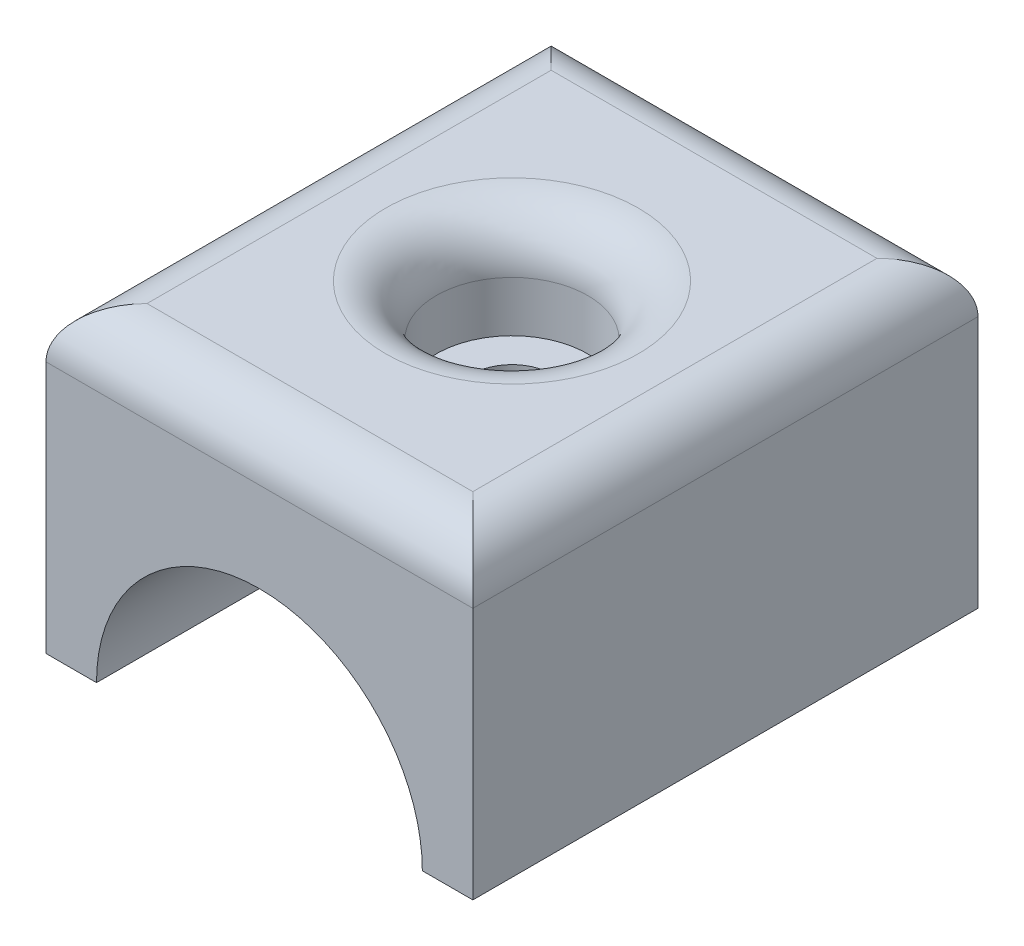
SolidWorks part; units mm, degrees
ref_plane "Front Plane" through (0, 0, 0) normal (0, 0, 1) x (1, 0, 0)
ref_plane "Top Plane" through (0, 0, 0) normal (0, 1, 0) x (1, 0, 0)
ref_plane "Right Plane" through (0, 0, 0) normal (1, 0, 0) x (0, 0, -1)
sketch "Sketch2" plane through (0, 0, 0) normal (0, 0, 1) x (1, 0, 0)
  line L0 (0, 0) -> (-2, 0)
  line L1 (-2, 0) -> (-2, 12)
  line L2 (-2, 12) -> (14.9, 12)
  line L3 (14.9, 12) -> (14.9, 0)
  line L4 (14.9, 0) -> (12.9, 0)
  arc A0 (0, 0) -> (12.9, 0) centre (6.45, 0) cw
  dimension "D1" = 6.45
  dimension "D2" = 2
  dimension "D3" = 2
  dimension "D4" = 12
extrude "Boss-Extrude1" add sketch "Sketch2" against normal blind 20
ref_plane "Plane1" through (0, 12, 0) normal (0, 1, 0) x (1, 0, 0)
sketch "Sketch3" plane through (0, 12, 0) normal (0, 1, 0) x (1, 0, 0)
  line L0 (14.9, 0) -> (-2, 0) construction
  line L1 (-2, 20) -> (-2, 0) construction
  circle A0 centre (6.45, 10) radius 1.6
  point P5 (6.45, 0)
  point P11 (-2, 10)
  dimension "D1" = 3.2
extrude "Cut-Extrude1" cut sketch "Sketch3" against normal blind 20
sketch "Sketch4" plane through (0, 12, 0) normal (0, 1, 0) x (1, 0, 0)
  circle A0 centre (6.45, 10) radius 3
extrude "Cut-Extrude2" cut sketch "Sketch4" against normal blind 4
fillet "Fillet5" radius 2 5 edges at (-2, 12, -10) (6.45, 12, -20) (14.9, 12, -10) (6.45, 12, 0) (6.45, 12, -7)
